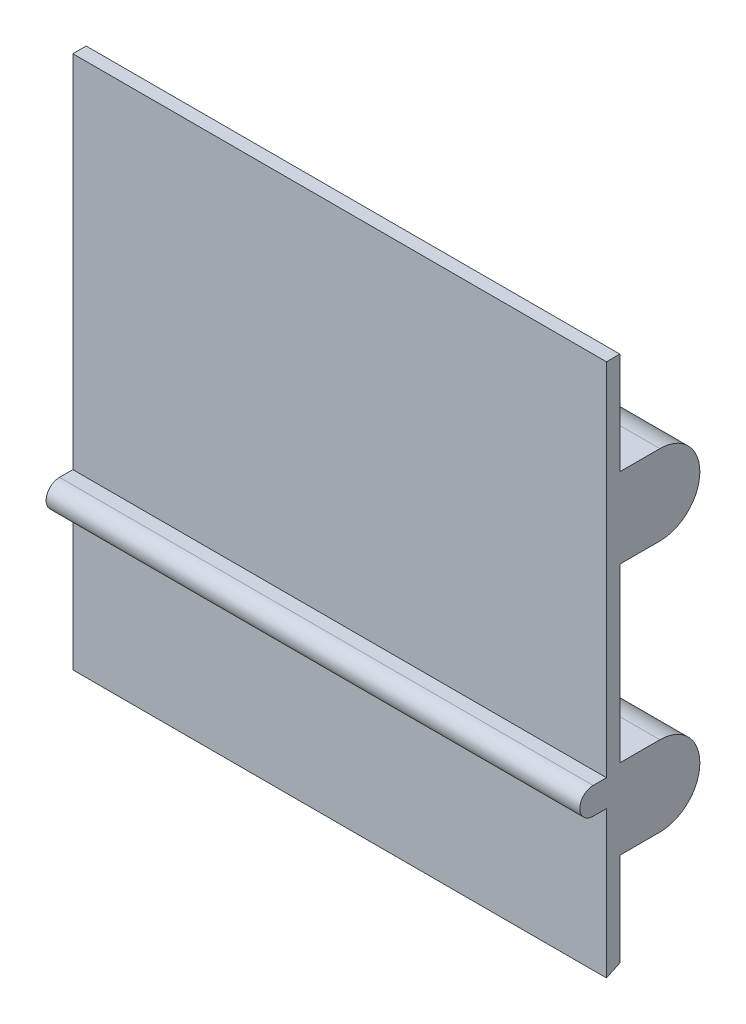
SolidWorks part; units mm, degrees
ref_plane "Front Plane" through (0, 0, 0) normal (0, 0, 1) x (1, 0, 0)
ref_plane "Top Plane" through (0, 0, 0) normal (0, 1, 0) x (1, 0, 0)
ref_plane "Right Plane" through (0, 0, 0) normal (1, 0, 0) x (0, 0, -1)
sketch "Sketch1" plane through (0, 0, 0) normal (0, 0, 1) x (1, 0, 0)
  line L1 (-63.5, 63.5) -> (63.5, 63.5)
  line L2 (-63.5, 63.5) -> (-63.5, -63.5)
  line L3 (-63.5, -63.5) -> (63.5, -63.5)
  line L4 (63.5, 63.5) -> (63.5, -63.5)
  line L5 (-63.5, 63.5) -> (63.5, -63.5) construction
  line L6 (-63.5, -63.5) -> (63.5, 63.5) construction
  point P0 (0, 0)
  dimension "D1" = 127
  dimension "D2" = 127
extrude "Boss-Extrude1" add sketch "Sketch1" along normal blind 3.175
sketch "Sketch2" plane through (63.5, 0, 0) normal (1, 0, 0) x (0, 0, -1)
  line L0 (-3.175, -63.5) -> (0, -62.0195)
  line L1 (-3.175, -63.5) -> (0, -63.5)
  line L2 (0, -63.5) -> (0, -62.0195)
  dimension "D1" = 25
extrude "Cut-Extrude1" cut sketch "Sketch2" against normal through all
sketch "Sketch3" plane through (63.5, 0, 0) normal (1, 0, 0) x (0, 0, -1)
  line L0 (0, -62.0195) -> (0, 63.5) construction
  line L1 (9.525, 39.2555) -> (0, 39.2555)
  line L2 (0, 39.2555) -> (0, 20.2055)
  line L3 (0, 20.2055) -> (9.525, 20.2055)
  line L4 (9.525, -20.7445) -> (0, -20.7445)
  line L5 (0, -20.7445) -> (0, -39.7945)
  line L6 (0, -39.7945) -> (9.525, -39.7945)
  arc A0 (9.525, 20.2055) -> (9.525, 39.2555) centre (9.525, 29.7305) ccw
  arc A2 (9.525, -39.7945) -> (9.525, -20.7445) centre (9.525, -30.2695) ccw
  dimension "D1" = 19.05
  dimension "D2" = 31.75
  dimension "D3" = 60
extrude "Boss-Extrude3" add sketch "Sketch3" against normal up to surface (127 mm away) up to face at (-63.5, 0.3701, 1.5875)
sketch "Sketch4" plane through (63.5, 0, 0) normal (1, 0, 0) x (0, 0, -1)
  line L0 (-3.175, -63.5) -> (-3.175, 63.5) construction
  line L1 (-6.35, -22.225) -> (-3.175, -22.225)
  line L2 (-6.35, -28.575) -> (-3.175, -28.575)
  line L3 (-3.175, -22.225) -> (-3.175, -28.575)
  arc A0 (-6.35, -22.225) -> (-6.35, -28.575) centre (-6.35, -25.4) ccw
  dimension "D1" = 6.35
  dimension "D2" = 38.1
extrude "Boss-Extrude4" add sketch "Sketch4" against normal up to surface (127 mm away) up to face at (-63.5, -0.0563, -4.2333)
